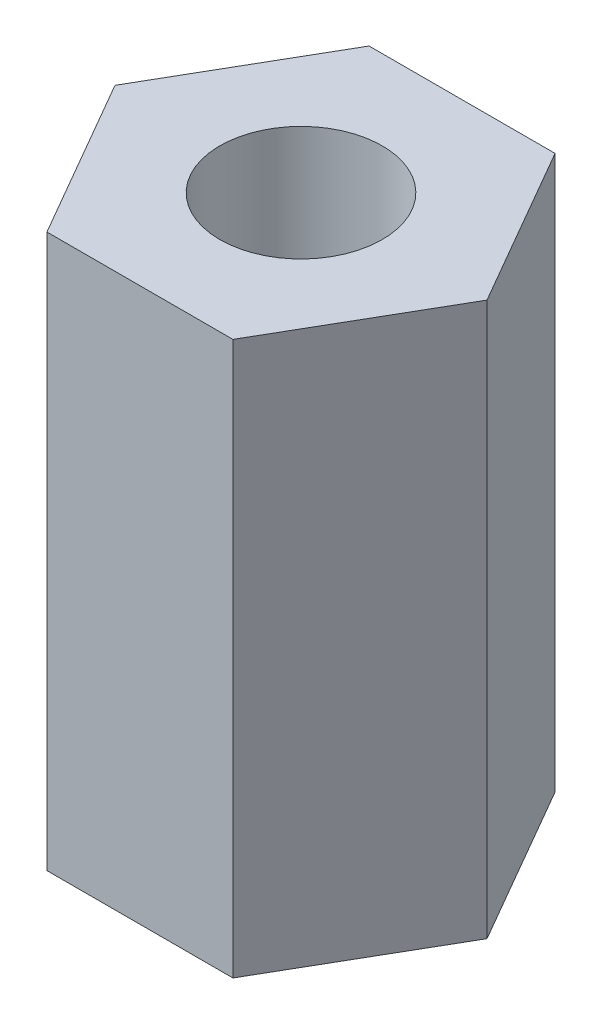
SolidWorks part; units mm, degrees
ref_plane "Front Plane" through (0, 0, 0) normal (0, 0, 1) x (1, 0, 0)
ref_plane "Top Plane" through (0, 0, 0) normal (0, 1, 0) x (1, 0, 0)
ref_plane "Right Plane" through (0, 0, 0) normal (1, 0, 0) x (0, 0, -1)
sketch "Sketch2" plane through (0, 0, 0) normal (0, 1, 0) x (1, 0, 0)
  line L1 (2.6905, 0) -> (1.3452, 2.33)
  line L2 (1.3452, 2.33) -> (-1.3452, 2.33)
  line L3 (-1.3452, 2.33) -> (-2.6905, 0)
  line L4 (-2.6905, 0) -> (-1.3452, -2.33)
  line L5 (-1.3452, -2.33) -> (1.3452, -2.33)
  line L6 (1.3452, -2.33) -> (2.6905, 0)
  circle A0 centre (0, 0) radius 2.33 construction
  circle A1 centre (0, 0) radius 1.175
  dimension "D2" = 2.35
  dimension "D1" = 4.66
extrude "Boss-Extrude2" add sketch "Sketch2" along normal blind 8
